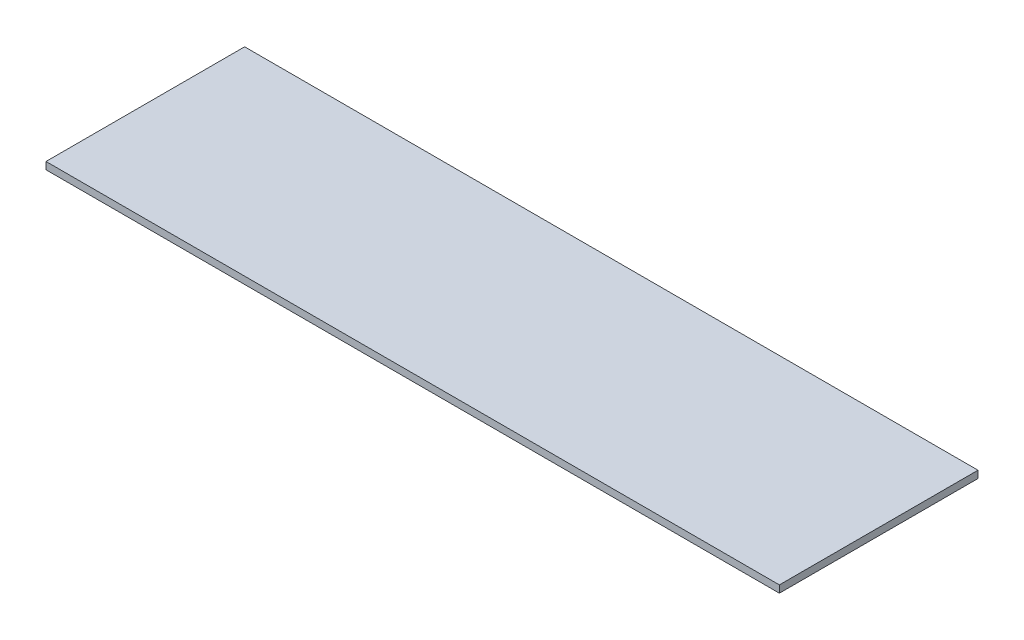
SolidWorks part; units mm, degrees
ref_plane "Front Plane" through (0, 0, 0) normal (0, 0, 1) x (1, 0, 0)
ref_plane "Top Plane" through (0, 0, 0) normal (0, 1, 0) x (1, 0, 0)
ref_plane "Right Plane" through (0, 0, 0) normal (1, 0, 0) x (0, 0, -1)
sketch "Sketch1" plane through (0, 0, 0) normal (0, 1, 0) x (1, 0, 0)
  line L1 (304.8, -82.55) -> (-304.8, -82.55)
  line L2 (304.8, -82.55) -> (304.8, 82.55)
  line L3 (304.8, 82.55) -> (-304.8, 82.55)
  line L4 (-304.8, -82.55) -> (-304.8, 82.55)
  line L5 (304.8, -82.55) -> (-304.8, 82.55) construction
  line L6 (304.8, 82.55) -> (-304.8, -82.55) construction
  point P0 (0, 0)
  dimension "D1" = 609.6
  dimension "D2" = 165.1
extrude "Boss-Extrude1" add sketch "Sketch1" along normal blind 6
